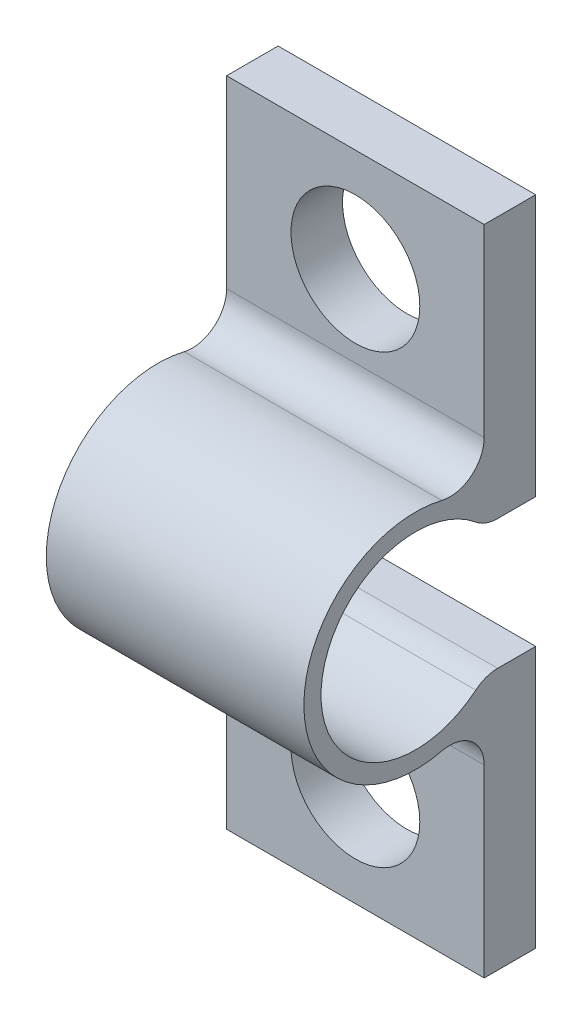
SolidWorks part; units mm, degrees
ref_plane "Front Plane" through (0, 0, 0) normal (0, 0, 1) x (1, 0, 0)
ref_plane "Top Plane" through (0, 0, 0) normal (0, 1, 0) x (1, 0, 0)
ref_plane "Right Plane" through (0, 0, 0) normal (1, 0, 0) x (0, 0, -1)
sketch "Sketch1" plane through (0, 0, 0) normal (0, 0, 1) x (1, 0, 0)
  line L1 (-35.5, -19) -> (-20.5, -19)
  line L2 (-35.5, -19) -> (-35.5, 19)
  line L3 (-35.5, 19) -> (-20.5, 19)
  line L5 (-35.5, -19) -> (0, 0) construction
  line L6 (-35.5, 19) -> (0, 0) construction
  line L11 (-20.5, 13) -> (-20.5, 19)
  line L12 (-20.5, 13) -> (-20.5, -19)
  circle A0 centre (-28, 13) radius 3.75
  circle A2 centre (-28, -13) radius 3.75
  point P0 (0, 0)
  point P14 (-16, -0.2346)
  point P19 (16, -0.2346)
  dimension "D5" = 7.5
  dimension "D8" = 7.5
  dimension "D3" = 6
  dimension "D4" = 7.5
  dimension "D10" = 7.5
  dimension "D11" = 6
  dimension "D13" = 7.5
extrude "Boss-Extrude1" add sketch "Sketch1" along normal blind 3 contours A0 | A2 | L1 L12 L11 L3 L2
sketch "Sketch8" plane through (-35.5, 0, 0) normal (-1, 0, 0) x (0, 0, 1)
  line L0 (3, -19) -> (3, 19) construction
  circle A0 centre (7, 0) radius 6.5
  circle A1 centre (7, 0) radius 5.5
  dimension "D1" = 13
  dimension "D2" = 11
  dimension "D3" = 4
extrude "Boss-Extrude4" add sketch "Sketch8" against normal blind 15
sketch "Sketch9" plane through (0, 0, 3) normal (0, 0, 1) x (1, 0, 0)
  line L1 (-35.5, 3.7749) -> (-20.5, 3.7749)
  line L2 (-35.5, 3.7749) -> (-35.5, -3.7749)
  line L3 (-35.5, -3.7749) -> (-20.5, -3.7749)
  line L4 (-20.5, 3.7749) -> (-20.5, -3.7749)
extrude "Cut-Extrude5" cut sketch "Sketch9" against normal blind 15
fillet "Fillet3" radius 2 2 edges at (-28, -5.1235, 3) (-28, 5.1235, 3)
fillet "Fillet4" radius 2 2 edges at (-28, -3.7749, 3) (-28, 3.7749, 3)
